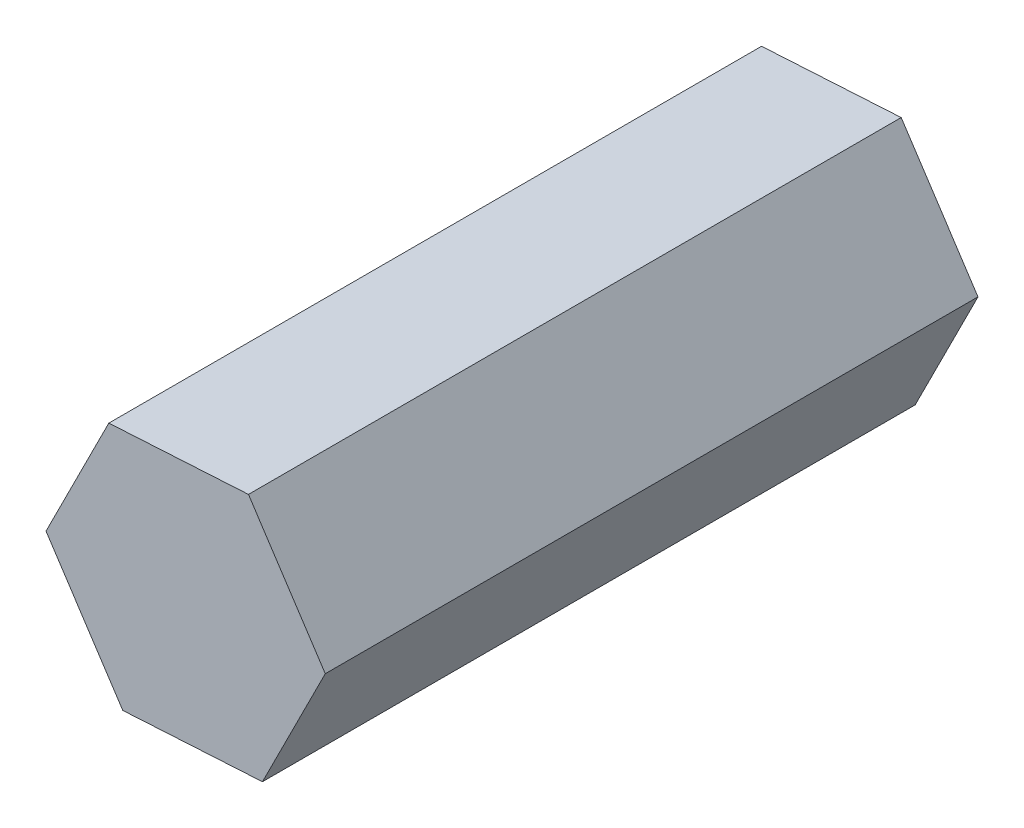
SolidWorks part; units mm, degrees
ref_plane "Plan de face" through (0, 0, 0) normal (0, 0, 1) x (1, 0, 0)
ref_plane "Plan de dessus" through (0, 0, 0) normal (0, 1, 0) x (1, 0, 0)
ref_plane "Plan de droite" through (0, 0, 0) normal (1, 0, 0) x (0, 0, -1)
sketch "Esquisse1" plane through (0, 0, 0) normal (0, 0, 1) x (1, 0, 0)
  line L1 (1.3475, 2.6803) -> (-1.6475, 2.5071)
  line L2 (-1.6475, 2.5071) -> (-2.995, -0.1732)
  line L3 (-2.995, -0.1732) -> (-1.3475, -2.6803)
  line L4 (-1.3475, -2.6803) -> (1.6475, -2.5071)
  line L5 (1.6475, -2.5071) -> (2.995, 0.1732)
  line L6 (2.995, 0.1732) -> (1.3475, 2.6803)
  circle A0 centre (0, 0) radius 2.5981 construction
  dimension "D1" = 3
extrude "Boss.-Extru.1" add sketch "Esquisse1" along normal blind 14
